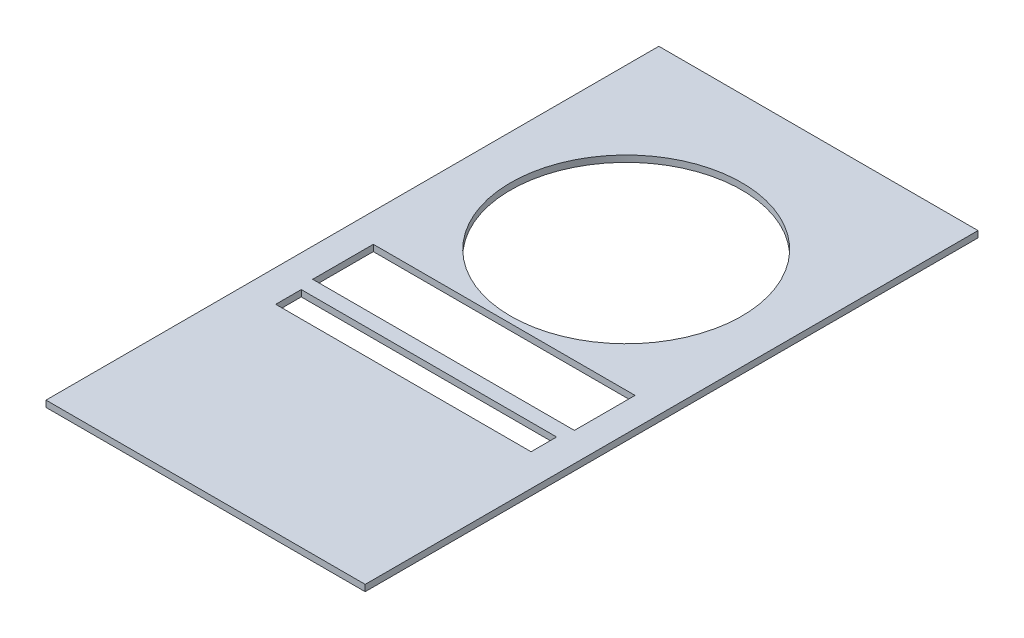
SolidWorks part; units mm, degrees
ref_plane "Front Plane" through (0, 0, 0) normal (0, 0, 1) x (1, 0, 0)
ref_plane "Top Plane" through (0, 0, 0) normal (0, 1, 0) x (1, 0, 0)
ref_plane "Right Plane" through (0, 0, 0) normal (1, 0, 0) x (0, 0, -1)
sketch "Sketch1" plane through (0, 0, 0) normal (0, 1, 0) x (1, 0, 0)
  line L0 (79.375, 266.7) -> (79.375, 304.8) construction
  line L1 (0, 0) -> (158.75, 0)
  line L2 (0, 0) -> (0, 304.8)
  line L3 (0, 304.8) -> (158.75, 304.8)
  line L4 (158.75, 0) -> (158.75, 304.8)
  line L5 (14.2875, 148.5136) -> (144.4625, 148.5136)
  line L6 (14.2875, 148.5136) -> (14.2875, 118.3511)
  line L7 (14.2875, 118.3511) -> (144.4625, 118.3511)
  line L8 (144.4625, 148.5136) -> (144.4625, 118.3511)
  line L9 (15.875, 98.3842) -> (142.875, 98.3842)
  line L10 (15.875, 98.3842) -> (15.875, 111.0842)
  line L11 (15.875, 111.0842) -> (142.875, 111.0842)
  line L12 (142.875, 98.3842) -> (142.875, 111.0842)
  circle A0 centre (79.375, 209.2) radius 57.5
  point P7 (79.375, 0)
  point P12 (79.375, 118.3511)
  point P17 (79.375, 98.3842)
  dimension "D3" = 115
  dimension "D8" = 38.1
  dimension "D1" = 158.75
  dimension "D2" = 304.8
  dimension "D4" = 130.175
  dimension "D5" = 30.1625
  dimension "D6" = 127
  dimension "D7" = 12.7
extrude "Boss-Extrude1" add sketch "Sketch1" along normal blind 3.175
